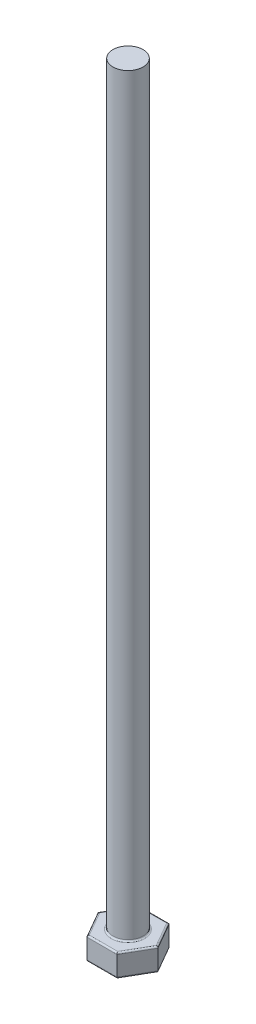
SolidWorks part; units mm, degrees
material "1060 Alloy"
ref_plane "Front Plane" through (0, 0, 0) normal (0, 0, 1) x (1, 0, 0)
ref_plane "Top Plane" through (0, 0, 0) normal (0, 1, 0) x (1, 0, 0)
ref_plane "Right Plane" through (0, 0, 0) normal (1, 0, 0) x (0, 0, -1)
sketch "Sketch1" plane through (0, 0, 0) normal (0, 1, 0) x (1, 0, 0)
  circle A1 centre (0, 0) radius 2
  dimension "D1" = 4
extrude "Boss-Extrude1" add sketch "Sketch1" along normal blind 100
sketch "Sketch2" plane through (0, 0, 0) normal (0, -1, 0) x (1, 0, 0)
  line L1 (3.9837, 0) -> (1.9919, 3.45)
  line L2 (1.9919, 3.45) -> (-1.9919, 3.45)
  line L3 (-1.9919, 3.45) -> (-3.9837, 0)
  line L4 (-3.9837, 0) -> (-1.9919, -3.45)
  line L5 (-1.9919, -3.45) -> (1.9919, -3.45)
  line L6 (1.9919, -3.45) -> (3.9837, 0)
  circle A0 centre (0, 0) radius 3.45 construction
  dimension "D1" = 6.9
extrude "Boss-Extrude2" add sketch "Sketch2" along normal blind 3
fillet "Fillet2" radius 0.2 13 edges at (0, -3, -3.45) (-2.9878, -3, -1.725) (-2.9878, -3, 1.725) (0, -3, 3.45) (2.9878, -3, 1.725) (2.9878, -3, -1.725) (2.9878, 0, 1.725) (0, 0, 3.45) (-2.9878, 0, 1.725) (-2.9878, 0, -1.725) (0, 0, -3.45) (2.9878, 0, -1.725) (0, 0, 2)
